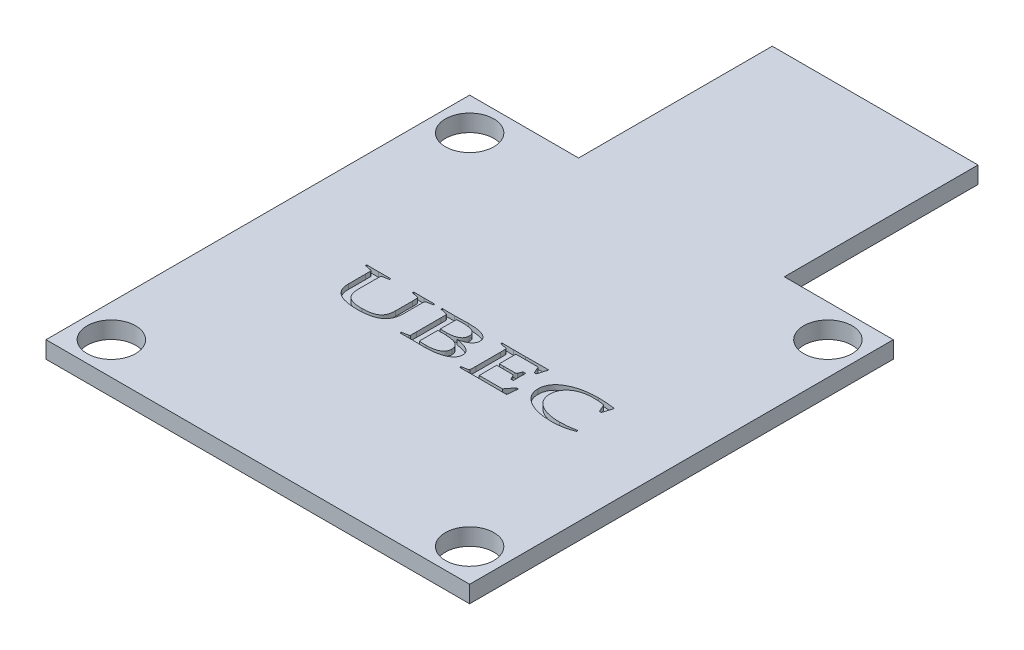
SolidWorks part; units mm, degrees
ref_plane "Front Plane" through (0, 0, 0) normal (0, 0, 1) x (1, 0, 0)
ref_plane "Top Plane" through (0, 0, 0) normal (0, 1, 0) x (1, 0, 0)
ref_plane "Right Plane" through (0, 0, 0) normal (1, 0, 0) x (0, 0, -1)
sketch "Sketch1" plane through (0, 0, 0) normal (0, 1, 0) x (1, 0, 0)
  line L0 (-8.5, 17.5) -> (-8.5, 33.5)
  line L1 (-17.5, -17.5) -> (17.5, -17.5)
  line L2 (-17.5, -17.5) -> (-17.5, 17.5)
  line L3 (-17.5, 17.5) -> (-8.5, 17.5)
  line L4 (17.5, -17.5) -> (17.5, 17.5)
  line L5 (-17.5, -17.5) -> (17.5, 17.5) construction
  line L6 (-17.5, 17.5) -> (17.5, -17.5) construction
  line L7 (-8.5, 33.5) -> (8.5, 33.5)
  line L8 (8.5, 33.5) -> (8.5, 17.5)
  line L9 (8.5, 17.5) -> (17.5, 17.5)
  circle A0 centre (14.8, 14.8) radius 2
  circle A1 centre (14.8, -14.8) radius 2
  circle A2 centre (-14.8, -14.8) radius 2
  circle A3 centre (-14.8, 14.8) radius 2
  point P0 (0, 0)
  point P6 (14.8, 14.8)
  point P9 (8.5, 17.5)
  point P10 (-8.5, 17.5)
  point P11 (-8.5, 33.5)
  point P18 (0, 0)
  point P19 (8.5, 33.5)
  dimension "D5" = 4
  dimension "D1" = 35
  dimension "D2" = 35
  dimension "D3" = 2.7
  dimension "D4" = 2.7
  dimension "D7" = 9
  dimension "D8" = 9
  dimension "D9" = 16
  dimension "D6" = 4
sketch "Sketch2" plane through (0, 0, 0) normal (0, 1, 0) x (1, 0, 0)
  text T0 "UBEC" font "Constantia" height 3.5
extrude "Boss-Extrude1" add sketch "Sketch1" against normal blind 1.4
extrude "Cut-Extrude3" cut sketch "Sketch2" against normal blind 0.4
